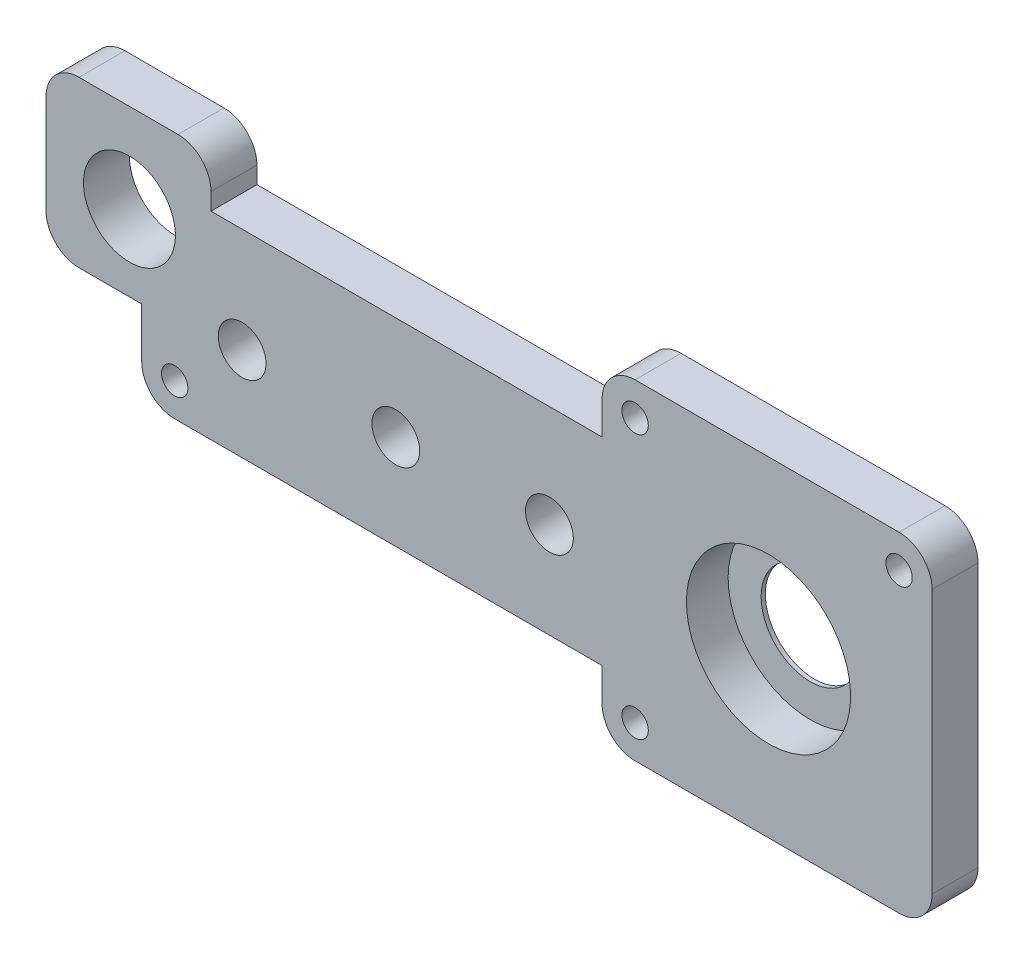
SolidWorks part; units mm, degrees
ref_plane "Front Plane" through (0, 0, 0) normal (0, 0, 1) x (1, 0, 0)
ref_plane "Top Plane" through (0, 0, 0) normal (0, 1, 0) x (1, 0, 0)
ref_plane "Right Plane" through (0, 0, 0) normal (1, 0, 0) x (0, 0, -1)
sketch "Sketch10" plane through (0, 0, 0) normal (0, 0, -1) x (-1, 0, 0)
  line L0 (-33.3871, 0.4566) -> (-54.6821, 21.7516) construction
  line L2 (-52.2874, 19.3569) -> (-52.2874, -15.6781) construction
  line L3 (11.8635, 18.2366) -> (-9.2571, 18.2366) construction
  line L4 (-9.2571, 18.2366) -> (1.3032, 23.5942) construction
  line L5 (1.3032, 23.5942) -> (1.3032, -17.7894) construction
  line L6 (2.4777, 0.4566) -> (-12.3051, 0.4566) construction
  line L7 (28.056, 6.8519) -> (41.4135, 20.2095) construction
  circle A0 centre (-33.3871, 0.4566) radius 4.7244
  circle A2 centre (-52.2874, -15.6781) radius 1.905
  circle A4 centre (28.056, 6.8519) radius 1.1793
  circle A5 centre (37.4743, 16.2702) radius 1.905
  circle A6 centre (-13.8463, 13.5969) radius 1.905
  circle A7 centre (-13.8463, -12.6838) radius 1.905
  circle A10 centre (27.2212, -14.6226) radius 2.032
  circle A11 centre (-50.815, 17.8845) radius 1.905
  circle A12 centre (16.4527, 13.5969) radius 1.905
sketch "Sketch4" plane through (0, 0, 0) normal (0, 0, 1) x (1, 0, 0)
  line L24 (-32.4508, 9.2023) -> (-41.9758, 9.2023)
  line L25 (-29.2758, 4.3944) -> (-29.2758, 6.0273)
  line L26 (8.3548, 4.3944) -> (-29.2758, 4.3944)
  line L27 (8.3548, 7.5694) -> (8.3548, 4.3944)
  line L28 (36.9298, 10.7444) -> (11.5298, 10.7444)
  line L29 (40.1048, -17.8306) -> (40.1048, 7.5694)
  line L30 (11.5298, -21.0056) -> (36.9298, -21.0056)
  line L31 (8.3548, -14.6556) -> (8.3548, -17.8306)
  line L32 (-32.7678, -14.6556) -> (8.3548, -14.6556)
  line L33 (-35.9428, -6.6727) -> (-35.9428, -11.4806)
  line L34 (-41.9758, -6.6727) -> (-35.9428, -6.6727)
  line L35 (-45.1508, 6.0273) -> (-45.1508, -3.4977)
  circle A2 centre (24.3673, -5.267) radius 4.7244
  arc A18 (-29.2758, 6.0273) -> (-32.4508, 9.2023) centre (-32.4508, 6.0273) ccw
  arc A19 (11.5298, 10.7444) -> (8.3548, 7.5694) centre (11.5298, 7.5694) ccw
  arc A20 (40.1048, 7.5694) -> (36.9298, 10.7444) centre (36.9298, 7.5694) ccw
  arc A21 (36.9298, -21.0056) -> (40.1048, -17.8306) centre (36.9298, -17.8306) ccw
  arc A22 (8.3548, -17.8306) -> (11.5298, -21.0056) centre (11.5298, -17.8306) ccw
  arc A23 (-35.9428, -11.4806) -> (-32.7678, -14.6556) centre (-32.7678, -11.4806) ccw
  arc A24 (-45.1508, -3.4977) -> (-41.9758, -6.6727) centre (-41.9758, -3.4977) ccw
  arc A25 (-41.9758, 9.2023) -> (-45.1508, 6.0273) centre (-41.9758, 6.0273) ccw
extrude "Stock" add sketch "Sketch4" against normal blind 4.4196 separate body
sketch "Sketch7" plane through (0, 0, 0) normal (0, 0, -1) x (-1, 0, 0)
  circle A2 centre (-24.3673, -5.267) radius 7.8994
extrude "CV Gear Well" cut sketch "Sketch7" along normal blind 4.0132
sketch "Sketch8" plane through (0, 0, 0) normal (0, 0, -1) x (-1, 0, 0)
  circle A2 centre (26.2788, -5.6649) radius 2.2987
  circle A4 centre (11.4964, -5.5487) radius 2.2987
  circle A6 centre (-3.2859, -5.4326) radius 2.2987
extrude "Idler Gear Well" cut sketch "Sketch8" along normal blind 4.2926
sketch "Sketch9" plane through (0, 0, 0) normal (0, 0, -1) x (-1, 0, 0)
  circle A2 centre (32.7678, -11.4806) radius 1.27
  circle A4 centre (-11.5298, -17.8306) radius 1.27
  circle A6 centre (-11.5298, 7.5694) radius 1.27
  circle A8 centre (-36.9298, 7.5694) radius 1.27
  circle A10 centre (37.1242, 0.6454) radius 4.4196
extrude "Outdrive Gear Well" cut sketch "Sketch9" along normal blind 4.4196
